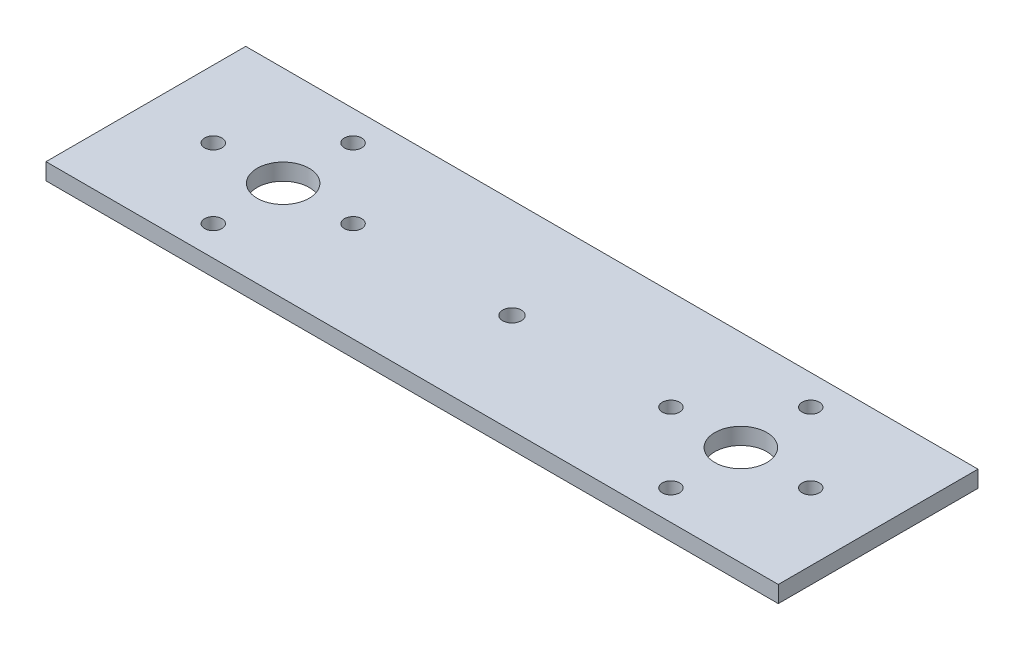
SolidWorks part; units mm, degrees
material "1023 Carbon Steel Sheet (SS)"
ref_plane "Front Plane" through (0, 0, 0) normal (0, 0, 1) x (1, 0, 0)
ref_plane "Top Plane" through (0, 0, 0) normal (0, 1, 0) x (1, 0, 0)
ref_plane "Right Plane" through (0, 0, 0) normal (1, 0, 0) x (0, 0, -1)
sketch "Sketch1" plane through (0, 0, 0) normal (0, 1, 0) x (1, 0, 0)
  line L1 (-139.7, -38.1) -> (139.7, -38.1)
  line L2 (-139.7, -38.1) -> (-139.7, 38.1)
  line L3 (-139.7, 38.1) -> (139.7, 38.1)
  line L4 (139.7, -38.1) -> (139.7, 38.1)
  line L5 (0, 38.1) -> (0, -38.1) construction
  line L6 (-139.7, 0) -> (139.7, 0) construction
  point P0 (0, 0)
  dimension "D1" = 76.2
  dimension "D2" = 279.4
extrude "Boss-Extrude1" add sketch "Sketch1" along normal blind 6.35
ref_plane "Plane1" through (0, 0, 0) normal (1, 0, 0) x (0, 0, -1)
hole_wizard "25/32 (0.78125) Diameter Hole1" positions "Sketch4" profile "Sketch5" hole size "25/32" standard "ANSI Inch" end condition through all
sketch "Sketch4" plane through (0, 6.35, 0) normal (0, 1, 0) x (1, 0, 0)
  line L1 (0, -27.94) -> (0, 27.94) construction
  point P0 (87.3125, 0)
  dimension "D2" = 87.3125
sketch "Sketch5" plane through (87.3125, 6.35, 0) normal (1, 0, 0) x (0, 0, 1)
  line L0 (0, 0) -> (0, 6.35)
  line L1 (0, 6.35) -> (9.9219, 6.35)
  line L2 (9.9219, 6.35) -> (9.9219, 0)
  line L5 (9.9219, 0) -> (0, 0)
  line L11 (0, -6.35) -> (0, 107.95) construction
  dimension "Thru Hole Dia." = 19.8438
  dimension "Thru Hole Depth" = 6.35
sketch "Sketch6" plane through (0, 6.35, 0) normal (0, 1, 0) x (1, 0, 0)
  circle A0 centre (60.6425, 0) radius 3.302
  circle A1 centre (87.3125, 0) radius 9.9219 construction
  dimension "D1" = 6.604
  dimension "D2" = 26.67
extrude "Cut-Extrude1" cut sketch "Sketch6" against normal blind 6.35
pattern_circular "CirPattern1" count 4 over 360 about axis through (87.3125, 0, 0) along (0, 1, 0) of "Cut-Extrude1"
mirror "Mirror2" about plane through (0, 0, 0) normal (1, 0, 0) of "CirPattern1", "25/32 (0.78125) Diameter Hole1", "Cut-Extrude1"
sketch "Sketch7" plane through (0, 0, 0) normal (0, -1, 0) x (-1, 0, 0)
  circle A0 centre (0, 0) radius 3.556
  dimension "D1" = 7.112
extrude "Cut-Extrude2" cut sketch "Sketch7" against normal blind 6.35
